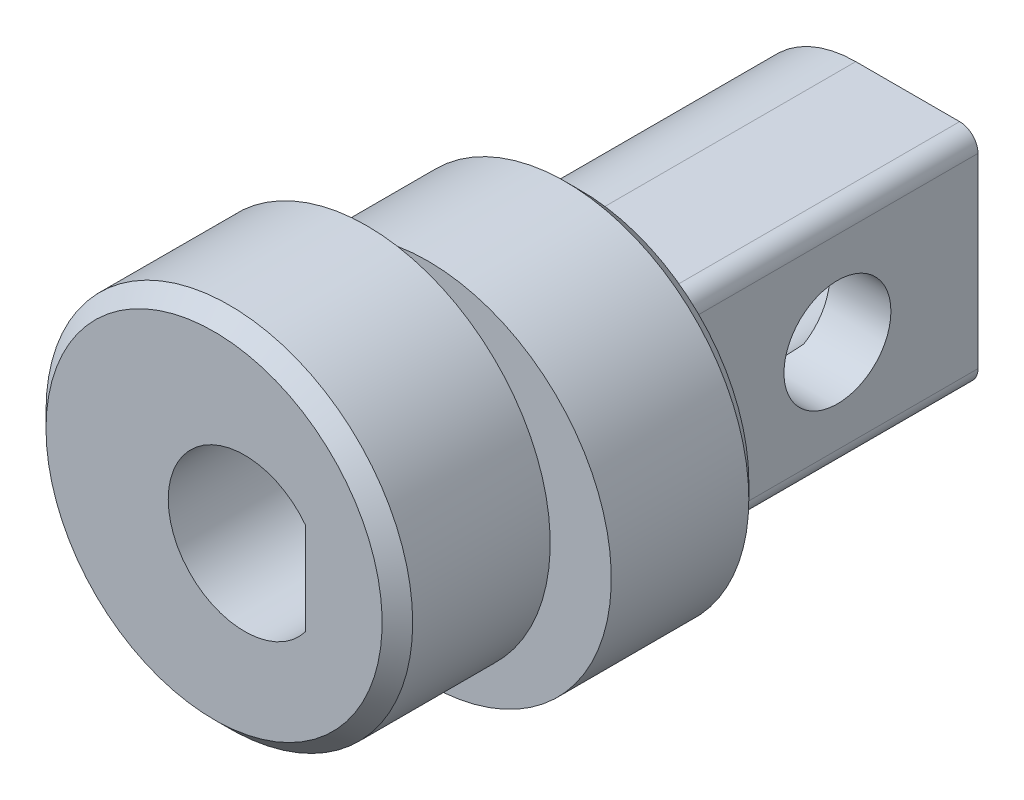
SolidWorks part; units mm, degrees
ref_plane "Ebene vorne" through (0, 0, 0) normal (0, 0, 1) x (1, 0, 0)
ref_plane "Ebene oben" through (0, 0, 0) normal (0, 1, 0) x (1, 0, 0)
ref_plane "Ebene rechts" through (0, 0, 0) normal (1, 0, 0) x (0, 0, -1)
ref_plane "Plane2" through (0, 0, 0.4) normal (0, 0, 1) x (1, 0, 0)
sketch "Sketch10" plane through (0, 0, 0.4) normal (0, 0, 1) x (1, 0, 0)
  circle A0 centre (0, 0) radius 6
  point P2 (0, 0)
  dimension "D1" = 12
extrude "Boss-Extrude4" add sketch "Sketch10" along normal blind 5
sketch "Sketch11" plane through (0, 0, 0.4) normal (0, 0, -1) x (-1, 0, 0)
  line L0 (-3, -3.05) -> (-3, 3.05)
  line L1 (-2.4, 3.65) -> (1, 3.65)
  line L2 (1, -3.65) -> (-2.4, -3.65)
  arc A2 (1, 3.65) -> (1, -3.65) centre (1, 0) cw
  arc A3 (-3, 3.05) -> (-2.4, 3.65) centre (-2.4, 3.05) cw
  arc A4 (-2.4, -3.65) -> (-3, -3.05) centre (-2.4, -3.05) cw
  point P0 (0.3733, 0)
  dimension "D1" = 3.65
  dimension "D3" = 0.6
  dimension "D4" = 1
  dimension "D2" = 4
extrude "Boss-Extrude5" add sketch "Sketch11" along normal blind 10
sketch "Sketch16" plane through (0, 0, 5.4) normal (0, 0, -1) x (-1, 0, 0)
  circle A0 centre (2, 0) radius 6
  dimension "D1" = 12
  dimension "D2" = 2
extrude "Boss-Extrude6" add sketch "Sketch16" against normal blind 5
sketch "Sketch17" plane through (0, 0, -9.6) normal (0, 0, 1) x (1, 0, 0)
  line L0 (1, -1.5) -> (1, 1.5)
  line L1 (-3.5, 0) -> (-3.5, 1.4955) construction
  arc A0 (1, 1.5) -> (1, -1.5) centre (-1, 0) ccw
  point P5 (-1, 0)
  dimension "D1" = 2.5
  dimension "D2" = 4.5
extrude "Cut-Extrude2" cut sketch "Sketch17" along normal through all
hole_wizard "Ø3.5 (3.5) Diameter Hole0" positions "Sketch19" profile "Sketch18" hole size "Ø3.5" standard "ANSI Metric"
sketch "Sketch19" plane through (3, 0, 0) normal (1, 0, 0) x (0, 0, -1)
  point P0 (5, 0)
sketch "Sketch18" plane through (3, 0, -5) normal (0, 1, 0) x (0, 0, -1)
  line L0 (0, 0) -> (0, 5.0515)
  line L1 (0, 5.0515) -> (1.75, 4)
  line L2 (1.75, 4) -> (1.75, 0)
  line L5 (1.75, 0) -> (0, 0)
  line L10 (0, 5.0515) -> (-1.75, 4) construction
  line L11 (0, -6.35) -> (0, 107.95) construction
  dimension "Hole Dia." = 3.5
  dimension "Hole Depth" = 4
  dimension "Drill Angle" = 118
chamfer "Chamfer2" distance 0.5 angle 45 2 edges at (-8, 0, 10.4) (6, 0, 0.4)
